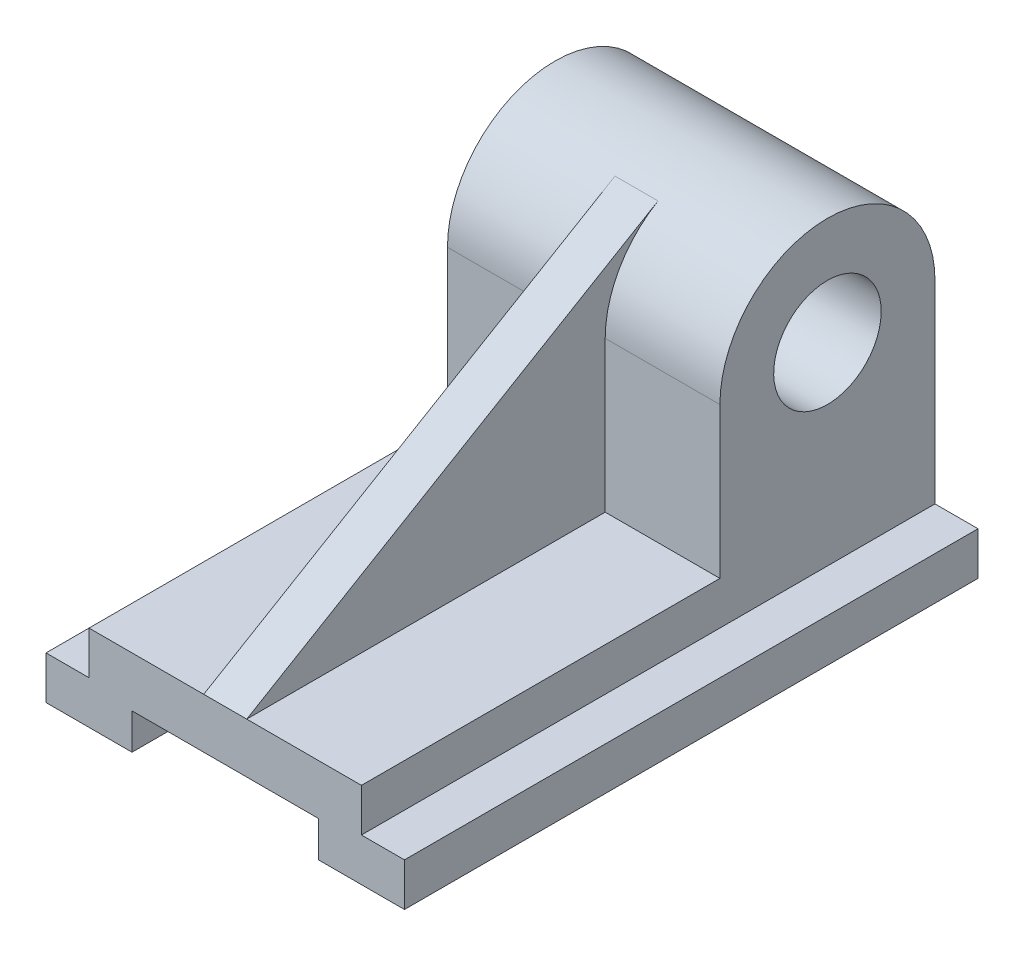
SolidWorks part; units mm, degrees
ref_plane "Front Plane" through (0, 0, 0) normal (0, 0, 1) x (1, 0, 0)
ref_plane "Top Plane" through (0, 0, 0) normal (0, 1, 0) x (1, 0, 0)
ref_plane "Right Plane" through (0, 0, 0) normal (1, 0, 0) x (0, 0, -1)
sketch "Sketch1" plane through (0, 0, 0) normal (0, 0, 1) x (1, 0, 0)
  line L0 (0, 0) -> (0, -12) construction
  line L1 (-50, 12) -> (50, 12)
  line L2 (-50, 12) -> (-50, -12)
  line L3 (-50, -12) -> (50, -12)
  line L4 (50, 12) -> (50, -12)
  line L5 (-50, 12) -> (50, -12) construction
  line L6 (-50, -12) -> (50, 12) construction
  line L7 (-50, 12) -> (-38, 12)
  line L8 (-50, 12) -> (-50, 0)
  line L9 (-50, 0) -> (-38, 0)
  line L10 (-38, 12) -> (-38, 0)
  line L11 (50, 12) -> (38, 12)
  line L12 (50, 12) -> (50, 0)
  line L13 (50, 0) -> (38, 0)
  line L14 (38, 12) -> (38, 0)
  line L15 (-26, -12) -> (26, -12)
  line L16 (-26, -12) -> (-26, -2)
  line L17 (-26, -2) -> (26, -2)
  line L18 (26, -12) -> (26, -2)
  point P0 (0, 0)
  dimension "D1" = 100
  dimension "D2" = 24
  dimension "D3" = 12
  dimension "D4" = 12
  dimension "D5" = 12
  dimension "D6" = 12
  dimension "D9" = 10
  dimension "D10" = 10
extrude "Boss-Extrude1" add sketch "Sketch1" along normal mid plane 160 contours L18 L3 L4 L13 L14 L1 L10 L9 L2 L16 L17
sketch "Sketch2" plane through (0, 12, 0) normal (0, 1, 0) x (1, 0, 0)
  line L0 (-38, 80) -> (38, 80) construction
  line L1 (-38, 80) -> (38, 80)
  line L2 (-38, 80) -> (-38, 20)
  line L3 (-38, 20) -> (38, 20)
  line L4 (38, 80) -> (38, 20)
  line L5 (-38, -80) -> (-38, 80) construction
  line L6 (38, -80) -> (38, 80) construction
  dimension "D1" = 60
extrude "Boss-Extrude2" add sketch "Sketch2" along normal blind 42
sketch "Sketch3" plane through (38, 0, 0) normal (1, 0, 0) x (0, 0, -1)
  line L0 (20, 54) -> (80, 54) construction
  circle A0 centre (50, 54) radius 30
  dimension "D2" = 60
extrude "Boss-Extrude4" add sketch "Sketch3" against normal up to surface (76 mm away) up to face at (-38, 22, -6.6667)
sketch "Sketch5" plane through (38, 0, 0) normal (1, 0, 0) x (0, 0, -1)
  circle A0 centre (50, 54) radius 15
  dimension "D1" = 30
extrude "Cut-Extrude3" cut sketch "Sketch5" against normal through all
sketch "Sketch6" plane through (0, 0, 0) normal (1, 0, 0) x (0, 0, -1)
  line L0 (-80, 12) -> (34.7334, 79.825)
  arc A0 (80, 54) -> (20, 54) centre (50, 54) ccw construction
rib "Rib1" sketch "Sketch6" sketch "Sketch6" thickness 12 extrusion direction parallel to sketch draft on no parameters "D1"=12
